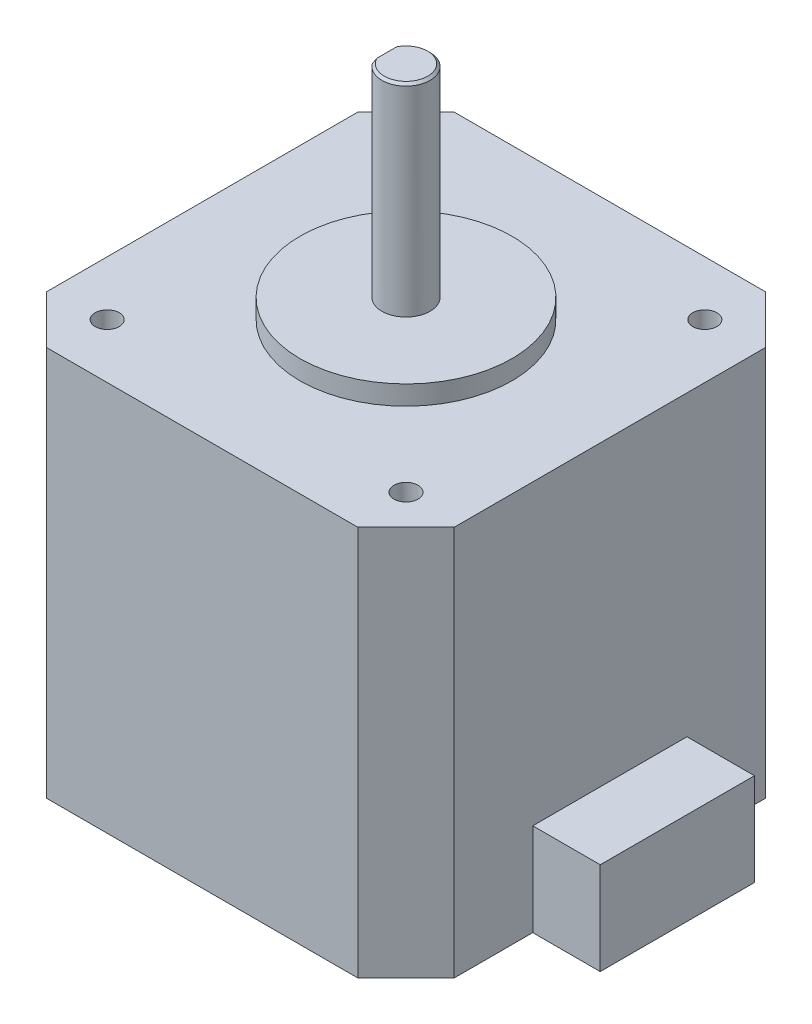
SolidWorks part; units mm, degrees
ref_plane "Front Plane" through (0, 0, 0) normal (0, 0, 1) x (1, 0, 0)
ref_plane "Top Plane" through (0, 0, 0) normal (0, 1, 0) x (1, 0, 0)
ref_plane "Right Plane" through (0, 0, 0) normal (1, 0, 0) x (0, 0, -1)
sketch "Sketch1" plane through (0, 0, 0) normal (0, 1, 0) x (1, 0, 0)
  line L1 (-21.15, 21.15) -> (21.15, 21.15)
  line L2 (-21.15, 21.15) -> (-21.15, -21.15)
  line L3 (-21.15, -21.15) -> (21.15, -21.15)
  line L4 (21.15, 21.15) -> (21.15, -21.15)
  line L5 (-21.15, 21.15) -> (21.15, -21.15) construction
  line L6 (-21.15, -21.15) -> (21.15, 21.15) construction
  point P0 (0, 0)
  dimension "D1" = 42.3
  dimension "D2" = 42.3
extrude "Boss-Extrude1" add sketch "Sketch1" along normal blind 40.5
hole_wizard "M3x0.5 Tapped Hole2" positions "Sketch5" profile "Sketch6" tap size "M3x0.5" standard "ANSI Metric"
sketch "Sketch5" plane through (0, 40.5, 0) normal (0, 1, 0) x (1, 0, 0)
  line L1 (-15.5, -15.5) -> (15.5, -15.5)
  line L2 (-15.5, -15.5) -> (-15.5, 15.5)
  line L3 (-15.5, 15.5) -> (15.5, 15.5)
  line L4 (15.5, -15.5) -> (15.5, 15.5)
  line L5 (-15.5, -15.5) -> (15.5, 15.5) construction
  line L6 (-15.5, 15.5) -> (15.5, -15.5) construction
  point P1 (0, 0)
  point P2 (15.5, 15.5)
  point P115 (-15.5, -15.5)
  point P116 (-15.5, 15.5)
  point P117 (15.5, -15.5)
  dimension "D1" = 31
  dimension "D2" = 31
sketch "Sketch6" plane through (0, 40.5, 0) normal (1, 0, 0) x (0, 0, 1)
  line L0 (0, 0) -> (0, 6.7511)
  line L1 (0, 6.7511) -> (1.25, 6)
  line L2 (1.25, 6) -> (1.25, 0)
  line L5 (1.25, 0) -> (0, 0)
  line L10 (0, 6.7511) -> (-1.25, 6) construction
  line L11 (0, -6.35) -> (0, 107.95) construction
  dimension "Tap Drill Dia." = 2.5
  dimension "Tap Drill Depth" = 6
  dimension "Drill Angle" = 118
cosmetic thread "Hole Thread1" parameters "D1"=4.5, "D2"=3
cosmetic thread "Hole Thread2" parameters "D1"=4.5, "D2"=3
cosmetic thread "Hole Thread3" parameters "D1"=4.5, "D2"=3
cosmetic thread "Hole Thread4" parameters "D1"=4.5, "D2"=3
cosmetic thread "Hole Thread5" parameters "D1"=4.5, "D2"=3
chamfer "Chamfer1" distance 5 angle 45 4 edges at (-21.15, 20.25, -21.15) (21.15, 20.25, -21.15) (21.15, 20.25, 21.15) (-21.15, 20.25, 21.15)
sketch "Sketch2" plane through (0, 40.5, 0) normal (0, 1, 0) x (1, 0, 0)
  circle A0 centre (0, 0) radius 11
  dimension "D1" = 22
extrude "Boss-Extrude2" add sketch "Sketch2" along normal blind 2
sketch "Sketch3" plane through (0, 40.5, 0) normal (0, 1, 0) x (1, 0, 0)
  circle A0 centre (0, 0) radius 2.5
  dimension "D1" = 5
extrude "Boss-Extrude3" add sketch "Sketch3" along normal blind 23
chamfer "Chamfer2" distance 0.25 angle 45 1 edges at (0, 63.5, 2.5)
sketch "Sketch7" plane through (0, 0, 0) normal (0, 0, 1) x (1, 0, 0)
  line L0 (2.5, 42.5) -> (2.5, 63.25) construction
  line L1 (-2.5, 63.5) -> (-2, 63.5)
  line L2 (-2.5, 63.5) -> (-2.5, 45.5)
  line L3 (-2.5, 45.5) -> (-2, 45.5)
  line L4 (-2, 63.5) -> (-2, 45.5)
  line L5 (2.25, 63.5) -> (-2.25, 63.5) construction
  dimension "D1" = 18
  dimension "D2" = 4.5
extrude "Cut-Extrude1" cut sketch "Sketch7" against normal through all both and the other way through all
sketch "Sketch4" plane through (21.15, 0, 0) normal (1, 0, 0) x (0, 0, -1)
  line L0 (-16.15, 0) -> (16.15, 0) construction
  line L1 (-8, 9.6) -> (8, 9.6)
  line L2 (-8, 9.6) -> (-8, 0)
  line L3 (-8, 0) -> (8, 0)
  line L4 (8, 9.6) -> (8, 0)
  line L5 (-8, 9.6) -> (8, 0) construction
  line L6 (-8, 0) -> (8, 9.6) construction
  point P0 (0, 4.8)
  dimension "D1" = 16
  dimension "D2" = 9.6
extrude "Boss-Extrude4" add sketch "Sketch4" along normal blind 7
